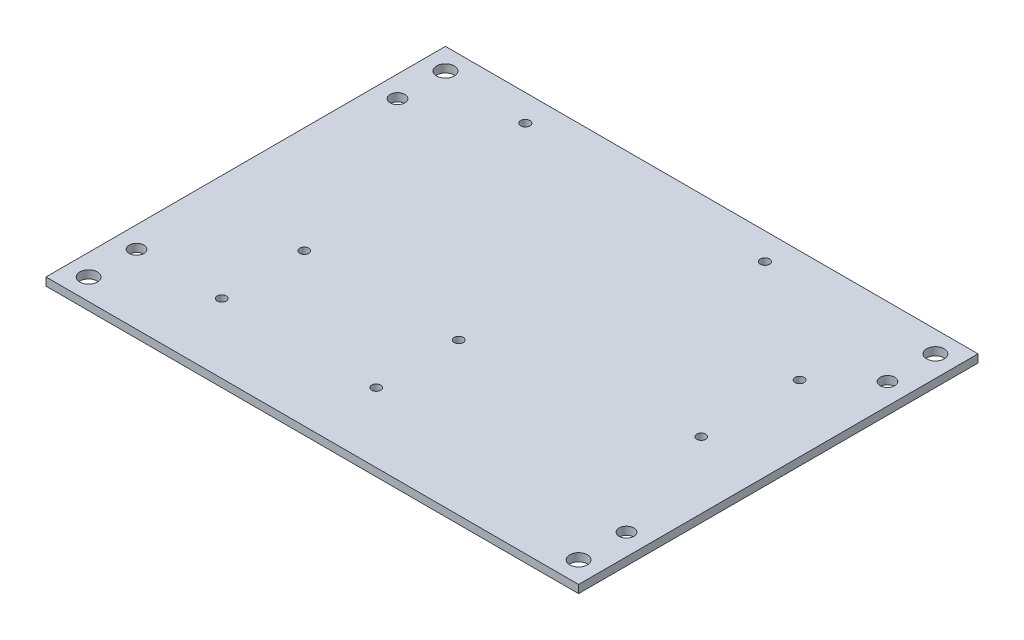
SolidWorks part; units mm, degrees
ref_plane "Front Plane" through (0, 0, 0) normal (0, 0, 1) x (1, 0, 0)
ref_plane "Top Plane" through (0, 0, 0) normal (0, 1, 0) x (1, 0, 0)
ref_plane "Right Plane" through (0, 0, 0) normal (1, 0, 0) x (0, 0, -1)
sketch "Sketch1" plane through (0, 0, 0) normal (0, 1, 0) x (1, 0, 0)
  line L1 (0, 0) -> (200, 0)
  line L2 (0, 0) -> (0, 150)
  line L3 (0, 150) -> (200, 150)
  line L4 (200, 0) -> (200, 150)
  dimension "D1" = 150
  dimension "D2" = 200
extrude "Boss-Extrude1" add sketch "Sketch1" along normal blind 3
sketch "Sketch2" plane through (0, 3, 0) normal (0, 1, 0) x (1, 0, 0)
  line L0 (100, 150) -> (100, 0) construction
  line L1 (200, 150) -> (0, 150) construction
  line L2 (0, 0) -> (200, 0) construction
  line L3 (0, 75) -> (200, 75) construction
  line L4 (0, 150) -> (0, 0) construction
  line L5 (200, 0) -> (200, 150) construction
  line L6 (175, 108) -> (175, 71.07) construction
  line L7 (40, 26) -> (98, 26) construction
  line L8 (40, 26) -> (40, 57) construction
  line L9 (40, 57) -> (98, 57) construction
  line L10 (98, 26) -> (98, 57) construction
  line L11 (40, 140) -> (130, 140) construction
  circle A0 centre (8, 142) radius 3.3
  circle A1 centre (8, 8) radius 3.3
  circle A2 centre (192, 8) radius 3.3
  circle A3 centre (192, 142) radius 3.3
  circle A4 centre (40, 57) radius 1.7
  circle A5 centre (98, 57) radius 1.7
  circle A6 centre (98, 26) radius 1.7
  circle A7 centre (40, 26) radius 1.7
  circle A10 centre (8, 124) radius 2.75
  circle A11 centre (8, 26) radius 2.75
  circle A12 centre (192, 26) radius 2.75
  circle A13 centre (192, 124) radius 2.75
  circle A14 centre (175, 108) radius 1.7
  circle A15 centre (175, 71.07) radius 1.7
  circle A16 centre (40, 140) radius 1.75
  circle A17 centre (130, 140) radius 1.75
  dimension "D3" = 6.6
  dimension "D6" = 3.4
  dimension "D9" = 42
  dimension "D13" = 5.5
  dimension "D15" = 8
  dimension "D8" = 3.4
  dimension "D17" = 3.5
  dimension "D1" = 8
  dimension "D2" = 8
  dimension "D4" = 58
  dimension "D5" = 31
  dimension "D7" = 36.93
  dimension "D10" = 26
  dimension "D11" = 40
  dimension "D12" = 25
  dimension "D14" = 18
  dimension "D16" = 90
  dimension "D18" = 10
  dimension "D19" = 40
extrude "Cut-Extrude1" cut sketch "Sketch2" against normal up to surface (3 mm away) up to face at (100, 0, -75)
